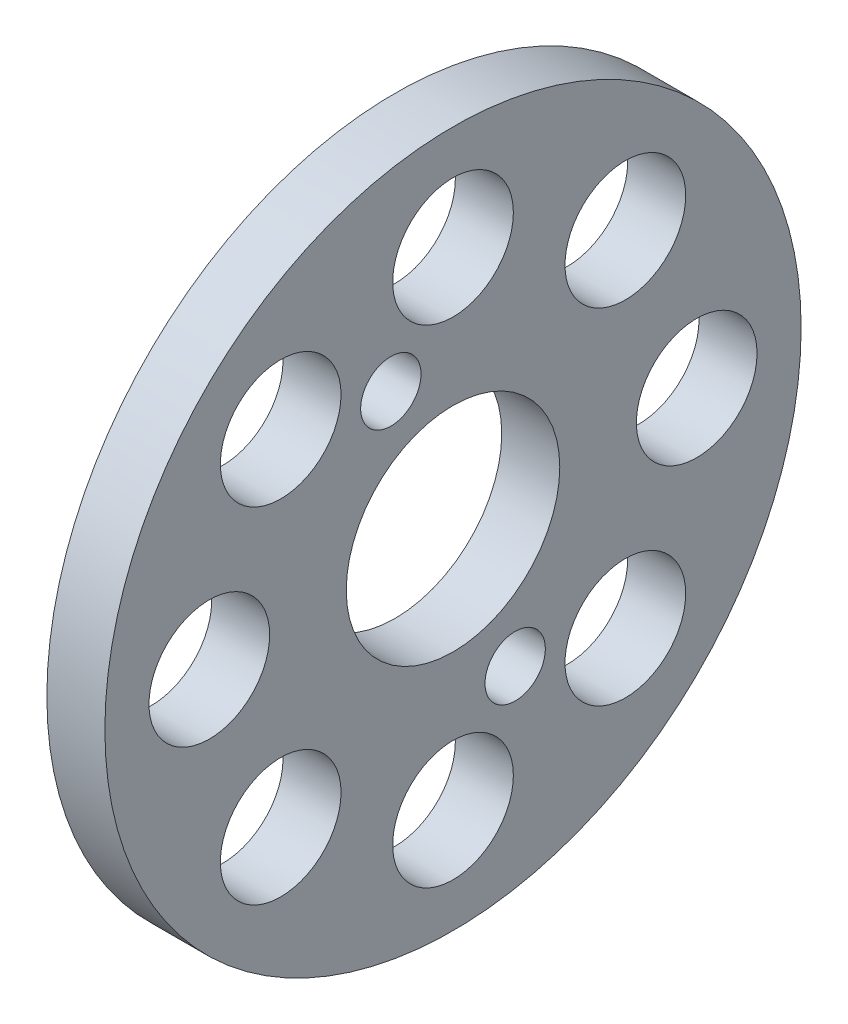
SolidWorks part; units mm, degrees
ref_plane "Front Plane" through (0, 0, 0) normal (0, 0, 1) x (1, 0, 0)
ref_plane "Top Plane" through (0, 0, 0) normal (0, 1, 0) x (1, 0, 0)
ref_plane "Right Plane" through (0, 0, 0) normal (1, 0, 0) x (0, 0, -1)
sketch "Axial profile (mm)" plane through (0, 0, 0) normal (0, 0, 1) x (1, 0, 0)
  line L0 (-110, 0) -> (75, 0) construction
  line L1 (143.7, 9.2) -> (148.7, 9.2)
  line L2 (148.7, 9.2) -> (148.7, 30)
  line L3 (148.7, 30) -> (143.7, 30)
  line L4 (143.7, 30) -> (143.7, 9.2)
revolve "Full revolution" add sketch "Axial profile (mm)" angle 360 about L0
sketch "Sketch2" plane through (0, 0, 0) normal (1, 0, 0) x (0, 0, -1)
  circle A0 centre (0, 21) radius 5.2
  circle A1 centre (-14.8492, 14.8492) radius 5.2
  circle A2 centre (-21, 0) radius 5.2
  circle A3 centre (-14.8492, -14.8492) radius 5.2
  circle A4 centre (0, -21) radius 5.2
  circle A5 centre (14.8492, -14.8492) radius 5.2
  circle A6 centre (21, 0) radius 5.2
  circle A7 centre (14.8492, 14.8492) radius 5.2
  circle A8 centre (-5.3576, 12.9343) radius 2.6
  circle A9 centre (5.3576, -12.9343) radius 2.6
extrude "Axial holes" cut sketch "Sketch2" against normal through all and the other way through all
